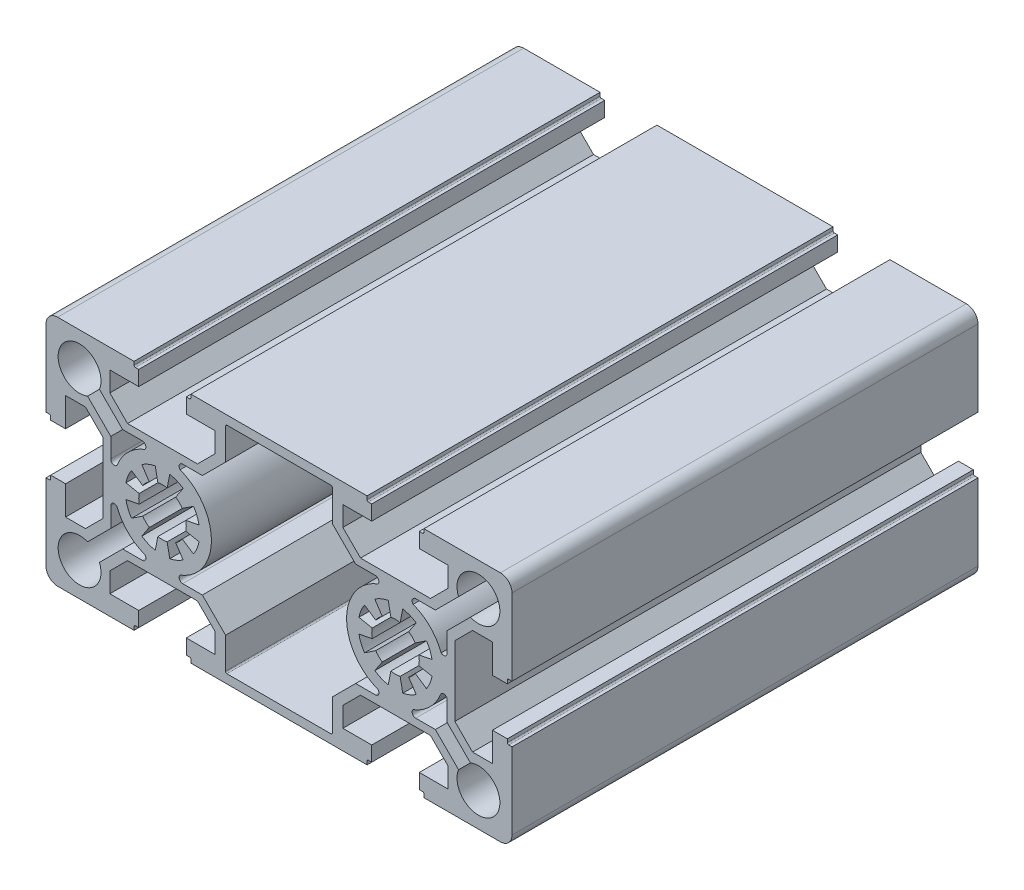
SolidWorks part; units mm, degrees
ref_plane "前视基准面" through (0, 0, 0) normal (0, 0, 1) x (1, 0, 0)
ref_plane "上视基准面" through (0, 0, 0) normal (0, 1, 0) x (1, 0, 0)
ref_plane "右视基准面" through (0, 0, 0) normal (1, 0, 0) x (0, 0, -1)
sketch "草图1" plane through (0, 0, 0) normal (0, 0, 1) x (1, 0, 0)
  line L0 (-31.5828, 26.0598) -> (-47.9828, 26.0598)
  line L1 (-50.4828, 23.5598) -> (-50.4828, 7.1598)
  line L2 (-30.5828, 21.8598) -> (-36.7828, 21.8598)
  line L3 (-30.5828, 25.0598) -> (-31.2828, 25.0598)
  line L4 (-31.5828, 25.3598) -> (-31.5828, 26.0598)
  line L5 (-50.4828, 7.1598) -> (-49.7828, 7.1598)
  line L6 (-49.4828, 6.8598) -> (-49.4828, 6.1598)
  line L7 (-36.7828, 21.8598) -> (-36.7828, 17.5924)
  line L8 (-30.5828, 25.0598) -> (-30.5828, 21.8598)
  line L9 (-36.5828, 5.3919) -> (-36.5828, 9.6142)
  line L10 (-29.9274, -5.5919) -> (-28.3162, -3.1807)
  line L11 (-27.0435, -6.7865) -> (-26.4778, -3.9422)
  line L12 (-23.9221, -6.7865) -> (-24.4878, -3.9422)
  line L13 (-21.0382, -5.5919) -> (-22.6494, -3.1807)
  line L14 (-18.8311, -3.3847) -> (-21.2423, -1.7736)
  line L15 (-17.6365, -0.5009) -> (-20.4808, 0.0649)
  line L16 (-17.6365, 2.6205) -> (-20.4808, 2.0548)
  line L17 (-18.8311, 5.5044) -> (-21.2423, 3.8932)
  line L18 (-21.0382, 7.7116) -> (-22.6494, 5.3003)
  line L19 (-23.9221, 8.9061) -> (-24.4878, 6.0618)
  line L20 (-27.0435, 8.9061) -> (-26.4778, 6.0618)
  line L21 (-29.9274, 7.7116) -> (-28.3162, 5.3003)
  line L22 (-32.1346, 5.5044) -> (-29.7233, 3.8932)
  line L23 (-33.3291, 2.6205) -> (-30.4848, 2.0548)
  line L24 (-33.3291, -0.5009) -> (-30.4848, 0.0649)
  line L25 (-32.1346, -3.3847) -> (-29.7233, -1.7736)
  line L26 (-41.5623, 14.5937) -> (-36.5828, 9.6142)
  line L27 (-36.7828, 17.5924) -> (-32.9828, 13.7924)
  line L28 (-39.0167, 17.1393) -> (-34.0372, 12.1598)
  line L29 (-29.8149, 12.1598) -> (-34.0372, 12.1598)
  line L30 (-25.4828, 13.7924) -> (-32.9828, 13.7924)
  line L31 (-19.3828, 26.0598) -> (-2.9828, 26.0598)
  line L32 (-11.9489, 17.1393) -> (-11.9489, 23.8598)
  line L33 (-11.6489, 24.1598) -> (-2.9828, 24.1598)
  line L34 (-20.3828, 21.8598) -> (-14.1828, 21.8598)
  line L35 (-20.3828, 25.0598) -> (-19.6828, 25.0598)
  line L36 (-19.3828, 25.3598) -> (-19.3828, 26.0598)
  line L37 (-14.1828, 21.8598) -> (-14.1828, 17.5924)
  line L38 (-20.3828, 25.0598) -> (-20.3828, 21.8598)
  line L39 (-14.1828, 17.5924) -> (-17.9828, 13.7924)
  line L40 (-25.4828, 13.7924) -> (-17.9828, 13.7924)
  line L41 (-31.5828, -23.9402) -> (-47.9828, -23.9402)
  line L42 (-50.4828, -21.4402) -> (-50.4828, -5.0402)
  line L43 (-30.5828, -22.9402) -> (-31.2828, -22.9402)
  line L44 (-31.5828, -23.2402) -> (-31.5828, -23.9402)
  line L45 (-50.4828, -5.0402) -> (-49.7828, -5.0402)
  line L46 (-49.4828, -4.7402) -> (-49.4828, -4.0402)
  line L47 (-19.3828, -23.9402) -> (-2.9828, -23.9402)
  line L48 (-11.9489, -15.0196) -> (-11.9489, -21.7402)
  line L49 (-11.6489, -22.0402) -> (-2.9828, -22.0402)
  line L50 (-20.3828, -22.9402) -> (-19.6828, -22.9402)
  line L51 (-19.3828, -23.2402) -> (-19.3828, -23.9402)
  line L52 (-30.5828, -19.7402) -> (-36.7828, -19.7402)
  line L53 (-36.7828, -19.7402) -> (-36.7828, -15.4728)
  line L54 (-30.5828, -22.9402) -> (-30.5828, -19.7402)
  line L55 (-36.7828, -15.4728) -> (-32.9828, -11.6728)
  line L56 (-25.4828, -11.6728) -> (-32.9828, -11.6728)
  line L57 (-20.3828, -19.7402) -> (-14.1828, -19.7402)
  line L58 (-14.1828, -19.7402) -> (-14.1828, -15.4728)
  line L59 (-20.3828, -22.9402) -> (-20.3828, -19.7402)
  line L60 (-14.1828, -15.4728) -> (-17.9828, -11.6728)
  line L61 (-25.4828, -11.6728) -> (-17.9828, -11.6728)
  line L62 (-46.2828, 6.1598) -> (-46.2828, 12.3598)
  line L63 (-46.2828, 12.3598) -> (-42.0154, 12.3598)
  line L64 (-49.4828, 6.1598) -> (-46.2828, 6.1598)
  line L65 (-42.0154, 12.3598) -> (-38.2154, 8.5598)
  line L66 (-38.2154, 1.0598) -> (-38.2154, 8.5598)
  line L67 (-46.2828, -4.0402) -> (-46.2828, -10.2402)
  line L68 (-46.2828, -10.2402) -> (-42.0154, -10.2402)
  line L69 (-49.4828, -4.0402) -> (-46.2828, -4.0402)
  line L70 (-42.0154, -10.2402) -> (-38.2154, -6.4402)
  line L71 (-38.2154, 1.0598) -> (-38.2154, -6.4402)
  line L72 (-11.9489, 17.1393) -> (-16.9284, 12.1598)
  line L73 (-21.1507, 12.1598) -> (-16.9284, 12.1598)
  line L74 (-36.5828, -3.2723) -> (-36.5828, -7.4946)
  line L75 (-41.5623, -12.4741) -> (-36.5828, -7.4946)
  line L76 (-39.0167, -15.0196) -> (-34.0372, -10.0402)
  line L77 (-29.8149, -10.0402) -> (-34.0372, -10.0402)
  line L78 (-11.9489, -15.0196) -> (-16.9284, -10.0402)
  line L79 (-21.1507, -10.0402) -> (-16.9284, -10.0402)
  line L80 (18.4172, 26.0598) -> (2.0172, 26.0598)
  line L81 (10.9833, 17.1393) -> (10.9833, 23.8598)
  line L82 (10.6833, 24.1598) -> (2.0172, 24.1598)
  line L83 (19.4172, 21.8598) -> (13.2172, 21.8598)
  line L84 (19.4172, 25.0598) -> (18.7172, 25.0598)
  line L85 (18.4172, 25.3598) -> (18.4172, 26.0598)
  line L86 (13.2172, 21.8598) -> (13.2172, 17.5924)
  line L87 (19.4172, 25.0598) -> (19.4172, 21.8598)
  line L88 (20.0726, -5.5919) -> (21.6838, -3.1807)
  line L89 (22.9565, -6.7865) -> (23.5222, -3.9422)
  line L90 (26.0779, -6.7865) -> (25.5122, -3.9422)
  line L91 (28.9618, -5.5919) -> (27.3506, -3.1807)
  line L92 (31.1689, -3.3847) -> (28.7577, -1.7736)
  line L93 (32.3635, -0.5009) -> (29.5192, 0.0649)
  line L94 (32.3635, 2.6205) -> (29.5192, 2.0548)
  line L95 (31.1689, 5.5044) -> (28.7577, 3.8932)
  line L96 (28.9618, 7.7116) -> (27.3506, 5.3003)
  line L97 (26.0779, 8.9061) -> (25.5122, 6.0618)
  line L98 (22.9565, 8.9061) -> (23.5222, 6.0618)
  line L99 (20.0726, 7.7116) -> (21.6838, 5.3003)
  line L100 (17.8654, 5.5044) -> (20.2767, 3.8932)
  line L101 (16.6709, 2.6205) -> (19.5152, 2.0548)
  line L102 (16.6709, -0.5009) -> (19.5152, 0.0649)
  line L103 (17.8654, -3.3847) -> (20.2767, -1.7736)
  line L104 (13.2172, 17.5924) -> (17.0172, 13.7924)
  line L105 (10.9833, 17.1393) -> (15.9628, 12.1598)
  line L106 (20.1851, 12.1598) -> (15.9628, 12.1598)
  line L107 (24.5172, 13.7924) -> (17.0172, 13.7924)
  line L108 (30.6172, 26.0598) -> (47.0172, 26.0598)
  line L109 (49.5172, 23.5598) -> (49.5172, 7.1598)
  line L110 (29.6172, 21.8598) -> (35.8172, 21.8598)
  line L111 (29.6172, 25.0598) -> (30.3172, 25.0598)
  line L112 (30.6172, 25.3598) -> (30.6172, 26.0598)
  line L113 (49.5172, 7.1598) -> (48.8172, 7.1598)
  line L114 (48.5172, 6.8598) -> (48.5172, 6.1598)
  line L115 (35.8172, 21.8598) -> (35.8172, 17.5924)
  line L116 (29.6172, 25.0598) -> (29.6172, 21.8598)
  line L117 (35.8172, 17.5924) -> (32.0172, 13.7924)
  line L118 (24.5172, 13.7924) -> (32.0172, 13.7924)
  line L119 (18.4172, -23.9402) -> (2.0172, -23.9402)
  line L120 (10.9833, -15.0196) -> (10.9833, -21.7402)
  line L121 (10.6833, -22.0402) -> (2.0172, -22.0402)
  line L122 (19.4172, -22.9402) -> (18.7172, -22.9402)
  line L123 (18.4172, -23.2402) -> (18.4172, -23.9402)
  line L124 (30.6172, -23.9402) -> (47.0172, -23.9402)
  line L125 (49.5172, -21.4402) -> (49.5172, -5.0402)
  line L126 (29.6172, -22.9402) -> (30.3172, -22.9402)
  line L127 (30.6172, -23.2402) -> (30.6172, -23.9402)
  line L128 (49.5172, -5.0402) -> (48.8172, -5.0402)
  line L129 (48.5172, -4.7402) -> (48.5172, -4.0402)
  line L130 (19.4172, -19.7402) -> (13.2172, -19.7402)
  line L131 (13.2172, -19.7402) -> (13.2172, -15.4728)
  line L132 (19.4172, -22.9402) -> (19.4172, -19.7402)
  line L133 (13.2172, -15.4728) -> (17.0172, -11.6728)
  line L134 (24.5172, -11.6728) -> (17.0172, -11.6728)
  line L135 (29.6172, -19.7402) -> (35.8172, -19.7402)
  line L136 (35.8172, -19.7402) -> (35.8172, -15.4728)
  line L137 (29.6172, -22.9402) -> (29.6172, -19.7402)
  line L138 (35.8172, -15.4728) -> (32.0172, -11.6728)
  line L139 (24.5172, -11.6728) -> (32.0172, -11.6728)
  line L140 (45.3172, 6.1598) -> (45.3172, 12.3598)
  line L141 (45.3172, 12.3598) -> (41.0498, 12.3598)
  line L142 (48.5172, 6.1598) -> (45.3172, 6.1598)
  line L143 (41.0498, 12.3598) -> (37.2498, 8.5598)
  line L144 (37.2498, 1.0598) -> (37.2498, 8.5598)
  line L145 (45.3172, -4.0402) -> (45.3172, -10.2402)
  line L146 (45.3172, -10.2402) -> (41.0498, -10.2402)
  line L147 (48.5172, -4.0402) -> (45.3172, -4.0402)
  line L148 (41.0498, -10.2402) -> (37.2498, -6.4402)
  line L149 (37.2498, 1.0598) -> (37.2498, -6.4402)
  line L150 (35.6172, 5.3919) -> (35.6172, 9.6142)
  line L151 (40.5967, 14.5937) -> (35.6172, 9.6142)
  line L152 (38.0511, 17.1393) -> (33.0716, 12.1598)
  line L153 (28.8493, 12.1598) -> (33.0716, 12.1598)
  line L154 (10.9833, -15.0196) -> (15.9628, -10.0402)
  line L155 (20.1851, -10.0402) -> (15.9628, -10.0402)
  line L156 (35.6172, -3.2723) -> (35.6172, -7.4946)
  line L157 (40.5967, -12.4741) -> (35.6172, -7.4946)
  line L158 (38.0511, -15.0196) -> (33.0716, -10.0402)
  line L159 (28.8493, -10.0402) -> (33.0716, -10.0402)
  line L160 (-2.9828, 26.0598) -> (2.0172, 26.0598)
  line L161 (-2.9828, 24.1598) -> (2.0172, 24.1598)
  line L162 (-2.9828, -23.9402) -> (2.0172, -23.9402)
  line L163 (-2.9828, -22.0402) -> (2.0172, -22.0402)
  arc A0 (-47.9828, 26.0598) -> (-50.4828, 23.5598) centre (-47.9828, 23.5598) ccw
  arc A1 (-31.5828, 25.3598) -> (-31.2828, 25.0598) centre (-31.2828, 25.3598) ccw
  arc A2 (-49.4828, 6.8598) -> (-49.7828, 7.1598) centre (-49.7828, 6.8598) ccw
  arc A3 (-26.4778, -3.9422) -> (-24.4878, -3.9422) centre (-25.4828, 1.0598) ccw
  arc A4 (-22.6494, -3.1807) -> (-21.2423, -1.7736) centre (-25.4828, 1.0598) ccw
  arc A5 (-20.4808, 0.0649) -> (-20.4808, 2.0548) centre (-25.4828, 1.0598) ccw
  arc A6 (-21.2423, 3.8932) -> (-22.6494, 5.3003) centre (-25.4828, 1.0598) ccw
  arc A7 (-24.4878, 6.0618) -> (-26.4778, 6.0618) centre (-25.4828, 1.0598) ccw
  arc A8 (-28.3162, 5.3003) -> (-29.7233, 3.8932) centre (-25.4828, 1.0598) ccw
  arc A9 (-30.4848, 2.0548) -> (-30.4848, 0.0649) centre (-25.4828, 1.0598) ccw
  arc A10 (-29.7233, -1.7736) -> (-28.3162, -3.1807) centre (-25.4828, 1.0598) ccw
  arc A11 (-29.9274, -5.5919) -> (-27.0435, -6.7865) centre (-25.4828, 1.0598) ccw
  arc A12 (-23.9221, -6.7865) -> (-21.0382, -5.5919) centre (-25.4828, 1.0598) ccw
  arc A13 (-18.8311, -3.3847) -> (-17.6365, -0.5009) centre (-25.4828, 1.0598) ccw
  arc A14 (-17.6365, 2.6205) -> (-18.8311, 5.5044) centre (-25.4828, 1.0598) ccw
  arc A15 (-21.0382, 7.7116) -> (-23.9221, 8.9061) centre (-25.4828, 1.0598) ccw
  arc A16 (-27.0435, 8.9061) -> (-29.9274, 7.7116) centre (-25.4828, 1.0598) ccw
  arc A17 (-32.1346, 5.5044) -> (-33.3291, 2.6205) centre (-25.4828, 1.0598) ccw
  arc A18 (-33.3291, -0.5009) -> (-32.1346, -3.3847) centre (-25.4828, 1.0598) ccw
  arc A19 (-29.2674, 10.854) -> (-35.277, 4.8444) centre (-25.4828, 1.0598) ccw
  arc A20 (-36.5828, 5.3919) -> (-35.277, 4.8444) centre (-35.8151, 5.3919) ccw
  arc A21 (-29.2674, 10.854) -> (-29.8149, 12.1598) centre (-29.8149, 11.3922) ccw
  arc A22 (-11.6489, 24.1598) -> (-11.9489, 23.8598) centre (-11.6489, 23.8598) ccw
  arc A23 (-19.6828, 25.0598) -> (-19.3828, 25.3598) centre (-19.6828, 25.3598) ccw
  arc A24 (-50.4828, -21.4402) -> (-47.9828, -23.9402) centre (-47.9828, -21.4402) ccw
  arc A25 (-31.2828, -22.9402) -> (-31.5828, -23.2402) centre (-31.2828, -23.2402) ccw
  arc A26 (-49.7828, -5.0402) -> (-49.4828, -4.7402) centre (-49.7828, -4.7402) ccw
  arc A27 (-11.9489, -21.7402) -> (-11.6489, -22.0402) centre (-11.6489, -21.7402) ccw
  arc A28 (-19.3828, -23.2402) -> (-19.6828, -22.9402) centre (-19.6828, -23.2402) ccw
  arc A29 (-39.0167, 17.1393) -> (-41.5623, 14.5937) centre (-43.2828, 18.8598) ccw
  arc A30 (-15.6886, 4.8444) -> (-21.6982, 10.854) centre (-25.4828, 1.0598) ccw
  arc A31 (-21.1507, 12.1598) -> (-21.6982, 10.854) centre (-21.1507, 11.3922) ccw
  arc A32 (-35.277, -2.7248) -> (-29.2674, -8.7344) centre (-25.4828, 1.0598) ccw
  arc A33 (-35.277, -2.7248) -> (-36.5828, -3.2723) centre (-35.8151, -3.2723) ccw
  arc A34 (-29.8149, -10.0402) -> (-29.2674, -8.7344) centre (-29.8149, -9.2725) ccw
  arc A35 (-41.5623, -12.4741) -> (-39.0167, -15.0196) centre (-43.2828, -16.7402) ccw
  arc A36 (-21.6982, -8.7344) -> (-15.6886, 4.8444) centre (-25.4828, 1.0598) ccw
  arc A37 (-21.6982, -8.7344) -> (-21.1507, -10.0402) centre (-21.1507, -9.2725) ccw
  arc A38 (10.9833, 23.8598) -> (10.6833, 24.1598) centre (10.6833, 23.8598) ccw
  arc A39 (18.4172, 25.3598) -> (18.7172, 25.0598) centre (18.7172, 25.3598) ccw
  arc A40 (23.5222, -3.9422) -> (25.5122, -3.9422) centre (24.5172, 1.0598) ccw
  arc A41 (27.3506, -3.1807) -> (28.7577, -1.7736) centre (24.5172, 1.0598) ccw
  arc A42 (29.5192, 0.0649) -> (29.5192, 2.0548) centre (24.5172, 1.0598) ccw
  arc A43 (28.7577, 3.8932) -> (27.3506, 5.3003) centre (24.5172, 1.0598) ccw
  arc A44 (25.5122, 6.0618) -> (23.5222, 6.0618) centre (24.5172, 1.0598) ccw
  arc A45 (21.6838, 5.3003) -> (20.2767, 3.8932) centre (24.5172, 1.0598) ccw
  arc A46 (19.5152, 2.0548) -> (19.5152, 0.0649) centre (24.5172, 1.0598) ccw
  arc A47 (20.2767, -1.7736) -> (21.6838, -3.1807) centre (24.5172, 1.0598) ccw
  arc A48 (20.0726, -5.5919) -> (22.9565, -6.7865) centre (24.5172, 1.0598) ccw
  arc A49 (26.0779, -6.7865) -> (28.9618, -5.5919) centre (24.5172, 1.0598) ccw
  arc A50 (31.1689, -3.3847) -> (32.3635, -0.5009) centre (24.5172, 1.0598) ccw
  arc A51 (32.3635, 2.6205) -> (31.1689, 5.5044) centre (24.5172, 1.0598) ccw
  arc A52 (28.9618, 7.7116) -> (26.0779, 8.9061) centre (24.5172, 1.0598) ccw
  arc A53 (22.9565, 8.9061) -> (20.0726, 7.7116) centre (24.5172, 1.0598) ccw
  arc A54 (17.8654, 5.5044) -> (16.6709, 2.6205) centre (24.5172, 1.0598) ccw
  arc A55 (16.6709, -0.5009) -> (17.8654, -3.3847) centre (24.5172, 1.0598) ccw
  arc A56 (20.7326, 10.854) -> (14.723, 4.8444) centre (24.5172, 1.0598) ccw
  arc A57 (20.7326, 10.854) -> (20.1851, 12.1598) centre (20.1851, 11.3922) ccw
  arc A58 (49.5172, 23.5598) -> (47.0172, 26.0598) centre (47.0172, 23.5598) ccw
  arc A59 (30.3172, 25.0598) -> (30.6172, 25.3598) centre (30.3172, 25.3598) ccw
  arc A60 (48.8172, 7.1598) -> (48.5172, 6.8598) centre (48.8172, 6.8598) ccw
  arc A61 (10.6833, -22.0402) -> (10.9833, -21.7402) centre (10.6833, -21.7402) ccw
  arc A62 (18.7172, -22.9402) -> (18.4172, -23.2402) centre (18.7172, -23.2402) ccw
  arc A63 (47.0172, -23.9402) -> (49.5172, -21.4402) centre (47.0172, -21.4402) ccw
  arc A64 (30.6172, -23.2402) -> (30.3172, -22.9402) centre (30.3172, -23.2402) ccw
  arc A65 (48.5172, -4.7402) -> (48.8172, -5.0402) centre (48.8172, -4.7402) ccw
  arc A66 (34.3114, 4.8444) -> (28.3018, 10.854) centre (24.5172, 1.0598) ccw
  arc A67 (34.3114, 4.8444) -> (35.6172, 5.3919) centre (34.8495, 5.3919) ccw
  arc A68 (28.8493, 12.1598) -> (28.3018, 10.854) centre (28.8493, 11.3922) ccw
  arc A69 (40.5967, 14.5937) -> (38.0511, 17.1393) centre (42.3172, 18.8598) ccw
  arc A70 (14.723, 4.8444) -> (20.7326, -8.7344) centre (24.5172, 1.0598) ccw
  arc A71 (20.1851, -10.0402) -> (20.7326, -8.7344) centre (20.1851, -9.2725) ccw
  arc A72 (28.3018, -8.7344) -> (34.3114, -2.7248) centre (24.5172, 1.0598) ccw
  arc A73 (35.6172, -3.2723) -> (34.3114, -2.7248) centre (34.8495, -3.2723) ccw
  arc A74 (28.3018, -8.7344) -> (28.8493, -10.0402) centre (28.8493, -9.2725) ccw
  arc A75 (38.0511, -15.0196) -> (40.5967, -12.4741) centre (42.3172, -16.7402) ccw
extrude "凸台-拉伸1" add sketch "草图1" along normal blind 100
